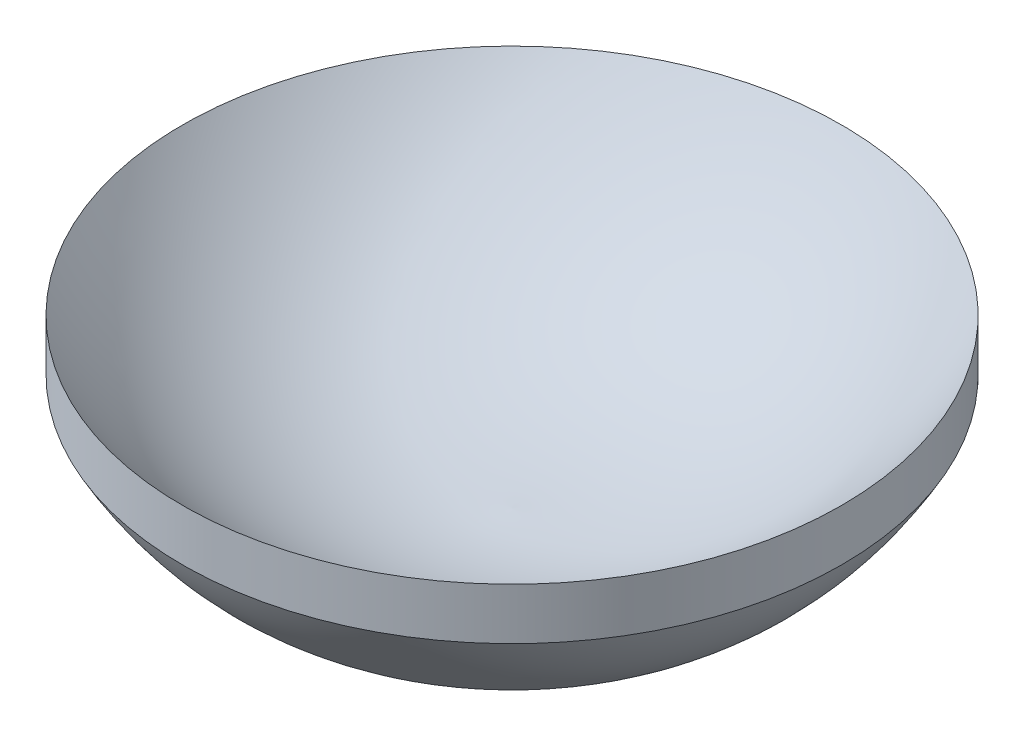
SolidWorks part; units mm, degrees
ref_plane "Front Plane" through (0, 0, 0) normal (0, 0, 1) x (1, 0, 0)
ref_plane "Top Plane" through (0, 0, 0) normal (0, 1, 0) x (1, 0, 0)
ref_plane "Right Plane" through (0, 0, 0) normal (1, 0, 0) x (0, 0, -1)
sketch "Sketch1" plane through (0, 0, 0) normal (0, 0, 1) x (1, 0, 0)
  line L0 (0, 0) -> (0, 38.1)
  line L1 (325.12, 152.4) -> (325.12, 203.2)
  spline S0 degree 2 poles (0, 0) (226.2955, -25.0935) (325.12, 152.4) knots 0 0 0 1 1 1
  spline S1 degree 2 poles (0, 38.1) (207.1408, 29.947) (325.12, 203.2) knots 0 0 0 1 1 1
  dimension "D1" = 325.12
  dimension "D2" = 50.8
  dimension "D3" = 38.1
  dimension "D4" = 203.2
revolve "Revolve1" add sketch "Sketch1" angle 360 about L0
